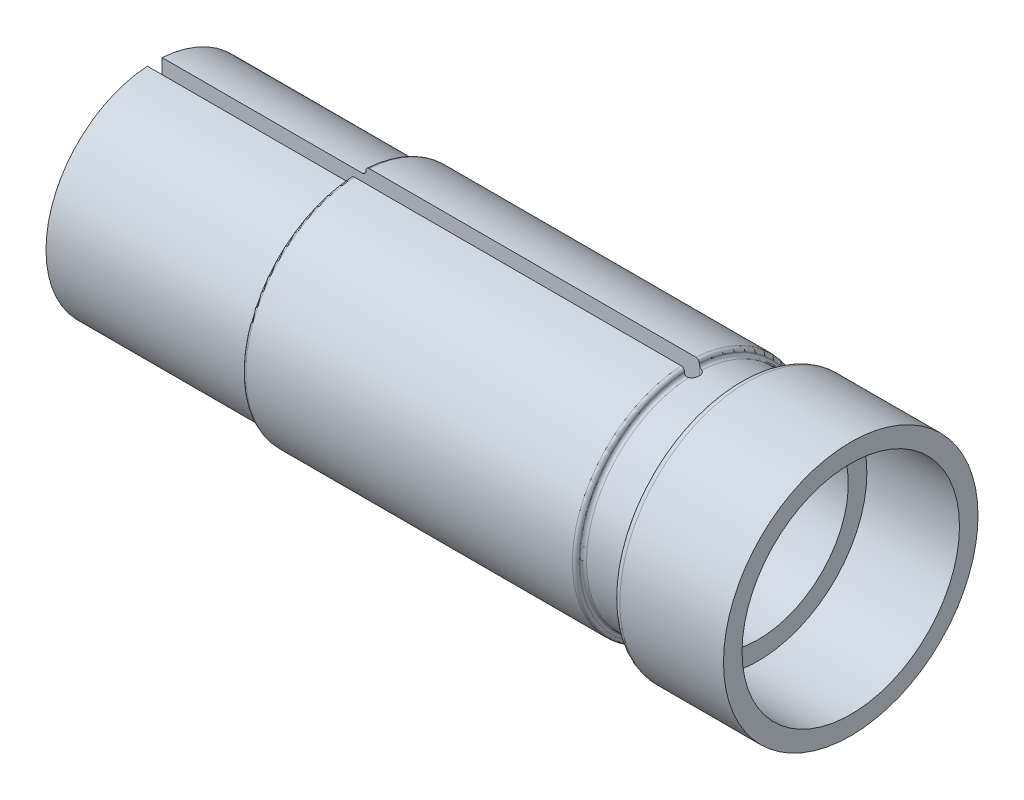
SolidWorks part; units mm, degrees
material "PVC 0.007 Plasticized"
ref_plane "Front" through (0, 0, 0) normal (0, 0, 1) x (1, 0, 0)
ref_plane "Top" through (0, 0, 0) normal (0, 1, 0) x (1, 0, 0)
ref_plane "Right" through (0, 0, 0) normal (1, 0, 0) x (0, 0, -1)
sketch "Sketch1" plane through (0, 0, 0) normal (0, 1, 0) x (1, 0, 0)
  line L0 (-16.2, 0) -> (16.2, 0) construction
  line L1 (-16.2, 8.655) -> (16.2, 8.655) construction
  line L2 (-16.2, 8.655) -> (-16.2, -8.655) construction
  line L3 (-16.2, -8.655) -> (16.2, -8.655) construction
  line L4 (16.2, 8.655) -> (16.2, -8.655) construction
  line L5 (-4, 0) -> (-4, 2.635) construction
  line L6 (-4, 2.635) -> (4, 2.635) construction
  line L7 (4, 2.635) -> (4, 0) construction
  line L8 (-10, 0) -> (-10, 2.435) construction
  line L9 (-10, 2.435) -> (-4, 2.435) construction
  line L10 (4, 2.435) -> (14.7, 2.435) construction
  line L11 (14.7, 2.435) -> (14.7, 0) construction
  line L12 (16.2, 2.935) -> (10.2, 2.935) construction
  line L13 (10.2, 2.935) -> (10.2, 0) construction
  line L14 (14.7, 2.935) -> (10.2, 2.935)
  line L15 (10.2, 2.935) -> (10.2, 2.435)
  line L16 (10.2, 2.435) -> (4, 2.435)
  line L17 (4, 2.435) -> (4, 2.635)
  line L18 (4, 2.635) -> (-4, 2.635)
  line L19 (-4, 2.635) -> (-4, 2.435)
  line L20 (-4, 2.435) -> (-10, 2.435)
  line L21 (14.7, 3.435) -> (9.9, 3.435)
  line L22 (9.7, 3.235) -> (9.7, 3.135)
  line L23 (9.5, 2.935) -> (4.59, 2.935)
  line L24 (4.5, 3.025) -> (4.5, 3.045)
  line L25 (4.41, 3.135) -> (-4.41, 3.135)
  line L26 (-4.5, 3.045) -> (-4.5, 3.025)
  line L27 (-4.59, 2.935) -> (-10, 2.935)
  line L28 (-10, 2.435) -> (-10, 2.935)
  line L29 (14.7, 3.435) -> (14.7, 2.935)
  line L30 (-4.5, 3.135) -> (-4.5, 2.935) construction
  line L31 (-4.5, 2.935) -> (-10, 2.935) construction
  line L32 (4.5, 3.135) -> (-4.5, 3.135) construction
  line L33 (9.7, 2.935) -> (4.5, 2.935) construction
  line L34 (4.5, 2.935) -> (4.5, 3.135) construction
  line L35 (9.7, 3.435) -> (9.7, 2.935) construction
  line L36 (14.7, 3.435) -> (9.7, 3.435) construction
  arc A0 (-4.5, 3.025) -> (-4.59, 2.935) centre (-4.59, 3.025) cw
  arc A1 (-4.41, 3.135) -> (-4.5, 3.045) centre (-4.41, 3.045) ccw
  arc A2 (4.59, 2.935) -> (4.5, 3.025) centre (4.59, 3.025) cw
  arc A3 (4.5, 3.045) -> (4.41, 3.135) centre (4.41, 3.045) ccw
  arc A4 (9.7, 3.135) -> (9.5, 2.935) centre (9.5, 3.135) cw
  arc A5 (9.9, 3.435) -> (9.7, 3.235) centre (9.9, 3.235) ccw
  point P5 (0, 2.635)
  dimension "D10" = 0.09
  dimension "D11" = 0.2
  dimension "D1" = 32.4
  dimension "D2" = 8
  dimension "D3" = 2.435
  dimension "D5" = 1.5
  dimension "D6" = 6
  dimension "D7" = 6
  dimension "D8" = 0.5
  dimension "D4" = 0.2
  dimension "D9" = 0.5
revolve "Revolve1" [suppressed] add sketch "Sketch1" angle 360 about L0
sketch "Sketch3" [suppressed] plane through (0, 0, 0) normal (0, 1, 0) x (1, 0, 0)
  line L0 (-10, 2.935) -> (-10, -2.935) construction
  line L1 (4.5, -3.025) -> (4.5, 3.025) construction
  line L2 (-10, 0.2) -> (4.5, 0.2)
  line L3 (-10, 0.2) -> (-10, -0.2)
  line L4 (-10, -0.2) -> (4.5, -0.2)
  line L5 (4.5, 0.2) -> (4.5, -0.2) construction
  line L6 (-10, 0.2) -> (4.5, -0.2) construction
  line L7 (-10, -0.2) -> (4.5, 0.2) construction
  arc A0 (4.5, -0.2) -> (4.5, 0.2) centre (4.5, 0) ccw
  point P6 (-2.75, 0)
  dimension "D1" = 0.4
extrude "Cut-Extrude2" [suppressed] cut sketch "Sketch3" along normal through all contours L2 A0 L4 L3
sketch "Sketch4" plane through (0, 0, 0) normal (0, 0, 1) x (1, 0, 0)
  line L0 (-16.2, 0) -> (16.2, 0) construction
  line L1 (-16.2, 8.6118) -> (16.2, 8.6118) construction
  line L2 (-16.2, 8.6118) -> (-16.2, -8.6118) construction
  line L3 (-16.2, -8.6118) -> (16.2, -8.6118) construction
  line L4 (16.2, 8.6118) -> (16.2, -8.6118) construction
  line L5 (-4, 0) -> (-4, 2.635) construction
  line L6 (-4, 2.635) -> (4, 2.635) construction
  line L7 (4, 2.635) -> (4, 0) construction
  line L8 (-10, 0) -> (-10, 2.435) construction
  line L9 (-10, 2.435) -> (-4, 2.435) construction
  line L10 (4, 2.435) -> (14.7, 2.435) construction
  line L11 (14.7, 2.435) -> (14.7, 0) construction
  line L12 (16.2, 2.935) -> (6.29, 2.935) construction
  line L13 (6.29, 2.935) -> (6.29, 0) construction
  line L14 (10.79, 2.935) -> (6.29, 2.935)
  line L15 (6.29, 2.935) -> (6.29, 2.435)
  line L16 (6.29, 2.435) -> (4, 2.435)
  line L17 (4, 2.435) -> (4, 2.635)
  line L18 (4, 2.635) -> (-4, 2.635)
  line L19 (-4, 2.635) -> (-4, 2.435)
  line L20 (-4, 2.435) -> (-10, 2.435)
  line L21 (10.79, 3.435) -> (5.99, 3.435)
  line L22 (5.79, 3.235) -> (5.79, 3.135)
  line L23 (5.59, 2.935) -> (4.59, 2.935)
  line L24 (4.5, 3.025) -> (4.5, 3.045)
  line L25 (4.41, 3.135) -> (-4.41, 3.135)
  line L26 (-4.5, 3.045) -> (-4.5, 3.025)
  line L27 (-4.59, 2.935) -> (-10, 2.935)
  line L28 (-10, 2.435) -> (-10, 2.935)
  line L29 (10.79, 3.435) -> (10.79, 2.935)
  line L30 (-4.5, 3.135) -> (-4.5, 2.935) construction
  line L31 (-4.5, 2.935) -> (-10, 2.935) construction
  line L32 (4.5, 3.135) -> (-4.5, 3.135) construction
  line L33 (5.79, 2.935) -> (4.5, 2.935) construction
  line L34 (4.5, 2.935) -> (4.5, 3.135) construction
  line L35 (5.79, 3.435) -> (5.79, 2.935) construction
  line L36 (10.79, 3.435) -> (5.79, 3.435) construction
  arc A0 (-4.5, 3.025) -> (-4.59, 2.935) centre (-4.59, 3.025) cw
  arc A1 (-4.41, 3.135) -> (-4.5, 3.045) centre (-4.41, 3.045) ccw
  arc A2 (4.59, 2.935) -> (4.5, 3.025) centre (4.59, 3.025) cw
  arc A3 (4.5, 3.045) -> (4.41, 3.135) centre (4.41, 3.045) ccw
  arc A4 (5.79, 3.135) -> (5.59, 2.935) centre (5.59, 3.135) cw
  arc A5 (5.99, 3.435) -> (5.79, 3.235) centre (5.99, 3.235) ccw
  dimension "D10" = 0.09
  dimension "D11" = 0.2
  dimension "D1" = 32.4
  dimension "D2" = 8
  dimension "D3" = 2.435
  dimension "D4" = 0.2
  dimension "D5" = 1.5
  dimension "D6" = 6
  dimension "D7" = 4.8
  dimension "D8" = 0.5
  dimension "D12" = 6.2
  dimension "D13" = 1
  dimension "D9" = 0.5
revolve "Revolve2" add sketch "Sketch4" angle 360 about L0
sketch "Sketch5" plane through (0, 0, 0) normal (0, 1, 0) x (1, 0, 0)
  line L2 (-10, 0.2) -> (4.5, 0.2)
  line L3 (-10, 0.2) -> (-10, -0.2)
  line L4 (-10, -0.2) -> (4.5, -0.2)
  line L5 (4.5, 0.2) -> (4.5, -0.2) construction
  line L6 (-10, 0.2) -> (4.5, -0.2) construction
  line L7 (-10, -0.2) -> (4.5, 0.2) construction
  arc A0 (4.5, -0.2) -> (4.5, 0.2) centre (4.5, 0) ccw
  point P6 (-2.75, 0)
  dimension "D1" = 0.4
extrude "Cut-Extrude3" cut sketch "Sketch5" along normal up to next contours L2 A0 L4 L3
sketch "Sketch6" plane through (10.79, 0, 0) normal (1, 0, 0) x (0, 0, -1)
  circle A0 centre (0, 0) radius 2.935
  circle A1 centre (0, 0) radius 3.435
  circle A2 centre (0, 0) radius 3.435 construction
  circle A3 centre (0, 0) radius 2.935 construction
extrude "Cut-Extrude4" cut sketch "Sketch6" against normal blind 2
equation "\"D7@Sketch1\"=\"D6@Sketch1\""
